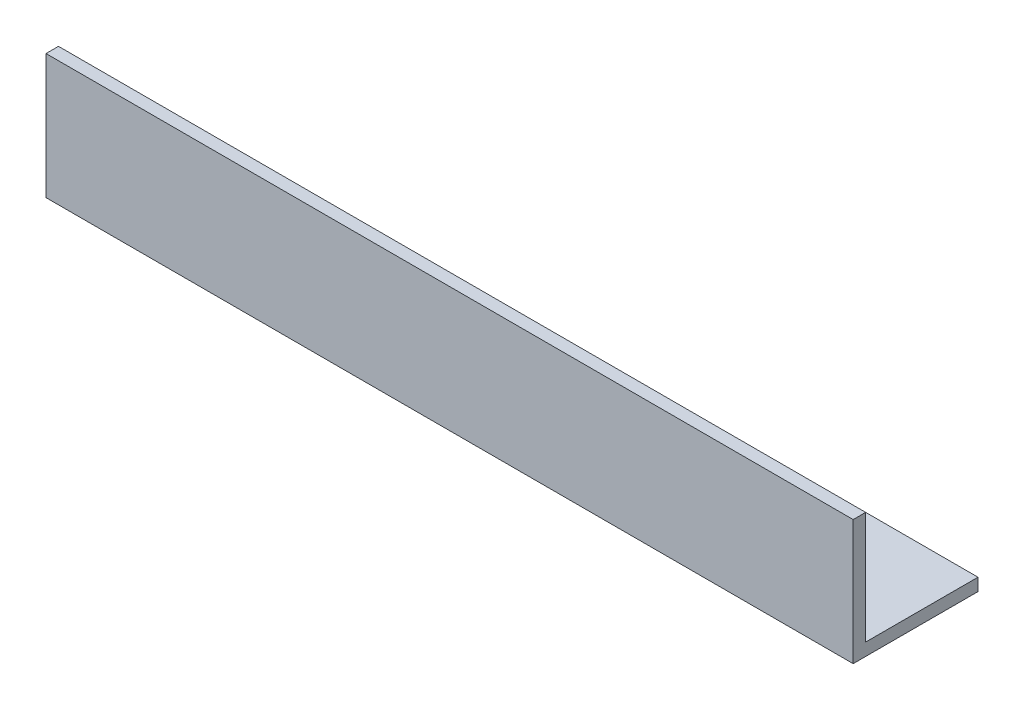
SolidWorks part; units mm, degrees
ref_plane "Спереди" through (0, 0, 0) normal (0, 0, 1) x (1, 0, 0)
ref_plane "Сверху" through (0, 0, 0) normal (0, 1, 0) x (1, 0, 0)
ref_plane "Справа" through (0, 0, 0) normal (1, 0, 0) x (0, 0, -1)
sketch "Эскиз1" plane through (0, 0, 0) normal (1, 0, 0) x (0, 0, -1)
  line L0 (0, 30) -> (0, 0)
  line L1 (0, 0) -> (30, 0)
extrude "Вытянуть-Тонкостенный1" add sketch "Эскиз1" along normal blind 194 thin thin type one direction reverse wall 3
